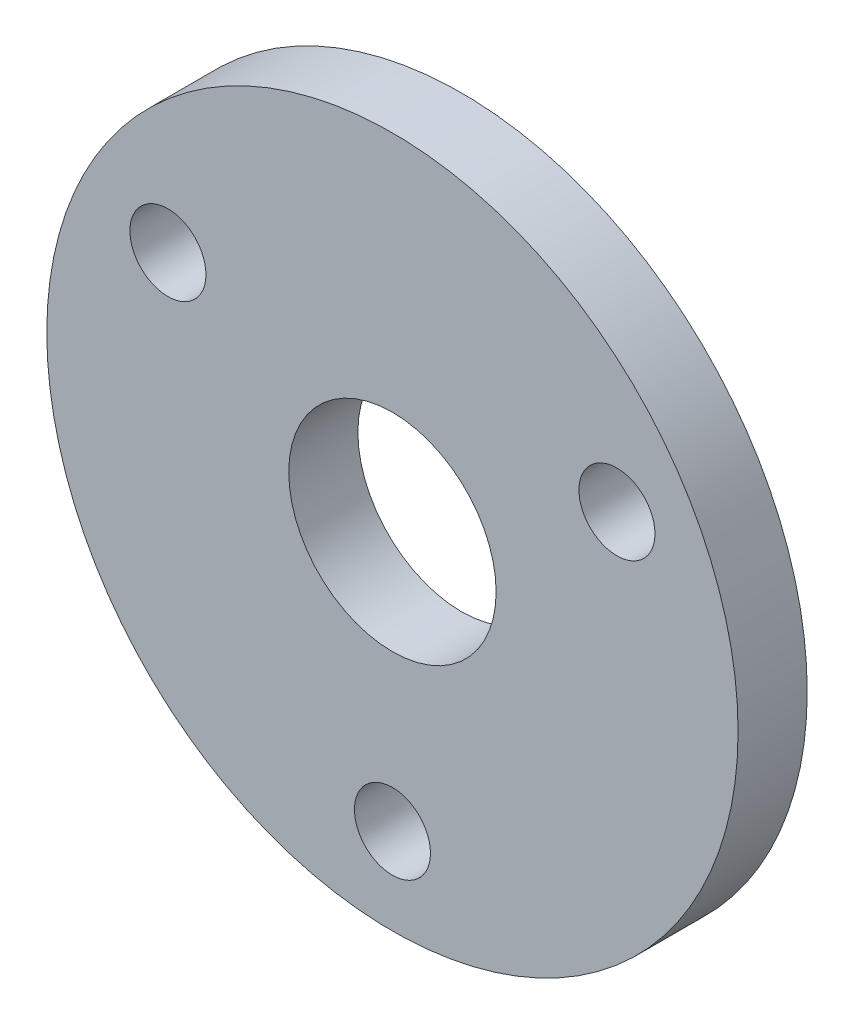
SolidWorks part; units mm, degrees
ref_plane "前视基准面" through (0, 0, 0) normal (0, 0, 1) x (1, 0, 0)
ref_plane "上视基准面" through (0, 0, 0) normal (0, 1, 0) x (1, 0, 0)
ref_plane "右视基准面" through (0, 0, 0) normal (1, 0, 0) x (0, 0, -1)
sketch "草图1" plane through (0, 0, 0) normal (0, 0, 1) x (1, 0, 0)
  line L0 (0, 0) -> (0, -7.5) construction
  circle A1 centre (0, 0) radius 10
  circle A2 centre (0, 0) radius 3
  circle A3 centre (0, -7.5) radius 1.1
  circle A4 centre (-6.4952, 3.75) radius 1.1
  circle A5 centre (6.4952, 3.75) radius 1.1
  point P17 (0, 0)
  dimension "D3" = 7.5
  dimension "D1" = 20
  dimension "D2" = 6
  dimension "D4" = 2.2
  dimension "D5" = 3
extrude "凸台-拉伸1" add sketch "草图1" along normal blind 2
